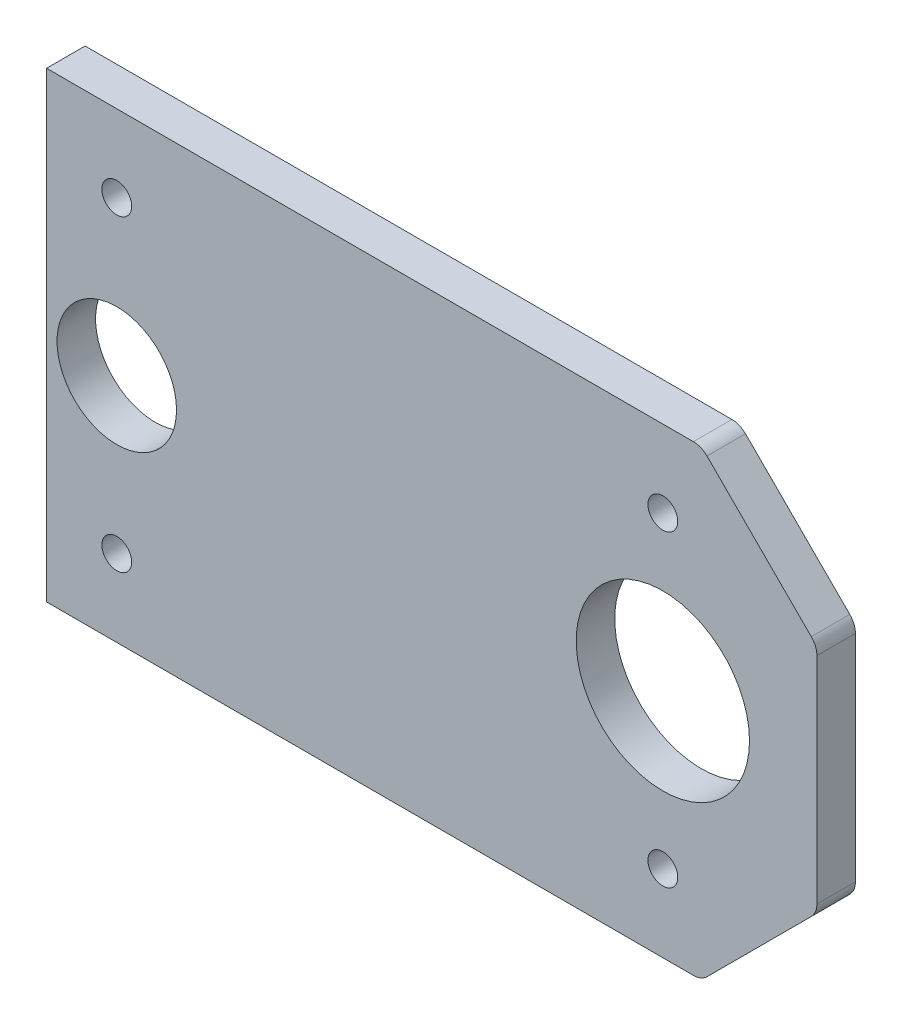
SolidWorks part; units mm, degrees
ref_plane "Front Plane" through (0, 0, 0) normal (0, 0, 1) x (1, 0, 0)
ref_plane "Top Plane" through (0, 0, 0) normal (0, 1, 0) x (1, 0, 0)
ref_plane "Right Plane" through (0, 0, 0) normal (1, 0, 0) x (0, 0, -1)
sketch "Sketch1" plane through (0, 0, 0) normal (0, 0, 1) x (1, 0, 0)
  line L1 (-63.5, 38.1) -> (63.5, 38.1)
  line L2 (-63.5, 38.1) -> (-63.5, -38.1)
  line L3 (-63.5, -38.1) -> (63.5, -38.1)
  line L4 (63.5, 38.1) -> (63.5, -38.1)
  line L5 (-63.5, 38.1) -> (63.5, -38.1) construction
  line L6 (-63.5, -38.1) -> (63.5, 38.1) construction
  point P0 (0, 0)
  dimension "D1" = 127
  dimension "D2" = 76.2
extrude "Boss-Extrude1" add sketch "Sketch1" along normal mid plane 6.35
sketch "Sketch2" plane through (0, 0, 3.175) normal (0, 0, 1) x (1, 0, 0)
  line L0 (-51.9252, 0) -> (38.1, 0) construction
  line L1 (63.5, -38.1) -> (63.5, 38.1) construction
  circle A0 centre (-51.9252, 0) radius 19.1008 construction
  circle A1 centre (38.1, 0) radius 19.1008 construction
  circle A2 centre (-51.9252, 0) radius 9.8489
  circle A3 centre (38.1, 0) radius 14.2875
  dimension "D1" = 38.2016
  dimension "D2" = 38.2016
  dimension "D4" = 28.575
  dimension "D6" = 19.6977
  dimension "D3" = 25.4
  dimension "D5" = 90.0252
extrude "Cut-Extrude1" cut sketch "Sketch2" against normal through all
chamfer "Chamfer1" distance 19.05 angle 45 2 edges at (63.5, 38.1, 0) (63.5, -38.1, 0)
hole_wizard "#10 (0.1935) Diameter Hole1" positions "Sketch4" profile "Sketch3" hole size "#10" standard "ANSI Inch" end condition through all
sketch "Sketch4" plane through (0, 0, 3.175) normal (0, 0, 1) x (1, 0, 0)
  line L1 (-51.9252, 25.4) -> (-51.9252, -25.4) construction
  line L3 (38.1, -25.4) -> (38.1, 25.4) construction
  circle A0 centre (-51.9252, 0) radius 9.8489 construction
  circle A1 centre (38.1, 0) radius 14.2875 construction
  point P0 (-51.9252, 25.4)
  point P2 (-51.9252, -25.4)
  point P4 (38.1, 25.4)
  point P6 (38.1, -25.4)
  point P19 (-51.9252, 0)
  point P24 (38.1, 0)
  dimension "D1" = 50.8
  dimension "D2" = 50.8
sketch "Sketch3" plane through (-51.9252, 25.4, 3.175) normal (1, 0, 0) x (0, -1, 0)
  line L0 (0, 0) -> (0, 6.35)
  line L1 (0, 6.35) -> (2.4574, 6.35)
  line L2 (2.4574, 6.35) -> (2.4574, 0)
  line L5 (2.4574, 0) -> (0, 0)
  line L11 (0, -6.35) -> (0, 107.95) construction
  dimension "Thru Hole Dia." = 4.9149
  dimension "Thru Hole Depth" = 6.35
fillet "Fillet1" radius 3.175 4 edges at (44.45, -38.1, 0) (63.5, -19.05, 0) (63.5, 19.05, 0) (44.45, 38.1, 0)
